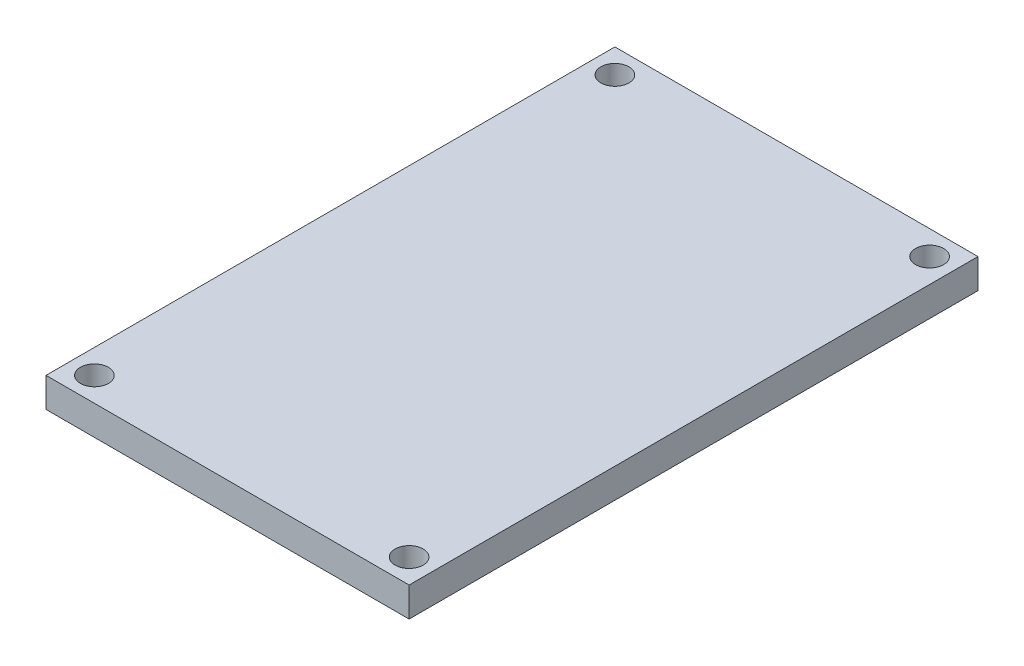
SolidWorks part; units mm, degrees
ref_plane "Front Plane" through (0, 0, 0) normal (0, 0, 1) x (1, 0, 0)
ref_plane "Top Plane" through (0, 0, 0) normal (0, 1, 0) x (1, 0, 0)
ref_plane "Right Plane" through (0, 0, 0) normal (1, 0, 0) x (0, 0, -1)
sketch "Sketch1" plane through (0, 0, 0) normal (0, 1, 0) x (1, 0, 0)
  line L0 (0, 29.845) -> (0, -29.845) construction
  line L1 (-19.05, 29.845) -> (19.05, 29.845)
  line L2 (-19.05, 29.845) -> (-19.05, -29.845)
  line L3 (-19.05, -29.845) -> (19.05, -29.845)
  line L4 (19.05, 29.845) -> (19.05, -29.845)
  line L5 (-19.05, 0) -> (19.05, 0) construction
  circle A0 centre (-16.51, 27.305) radius 1.4732
  circle A1 centre (16.51, 27.305) radius 1.4732
  circle A2 centre (-16.51, -27.305) radius 1.4732
  circle A3 centre (16.51, -27.305) radius 1.4732
  point P0 (0, 0)
  dimension "D3" = 2.9464
  dimension "D4" = 2.54
  dimension "D5" = 2.54
  dimension "D1" = 38.1
  dimension "D2" = 59.69
extrude "Boss-Extrude1" add sketch "Sketch1" along normal blind 3.0988
